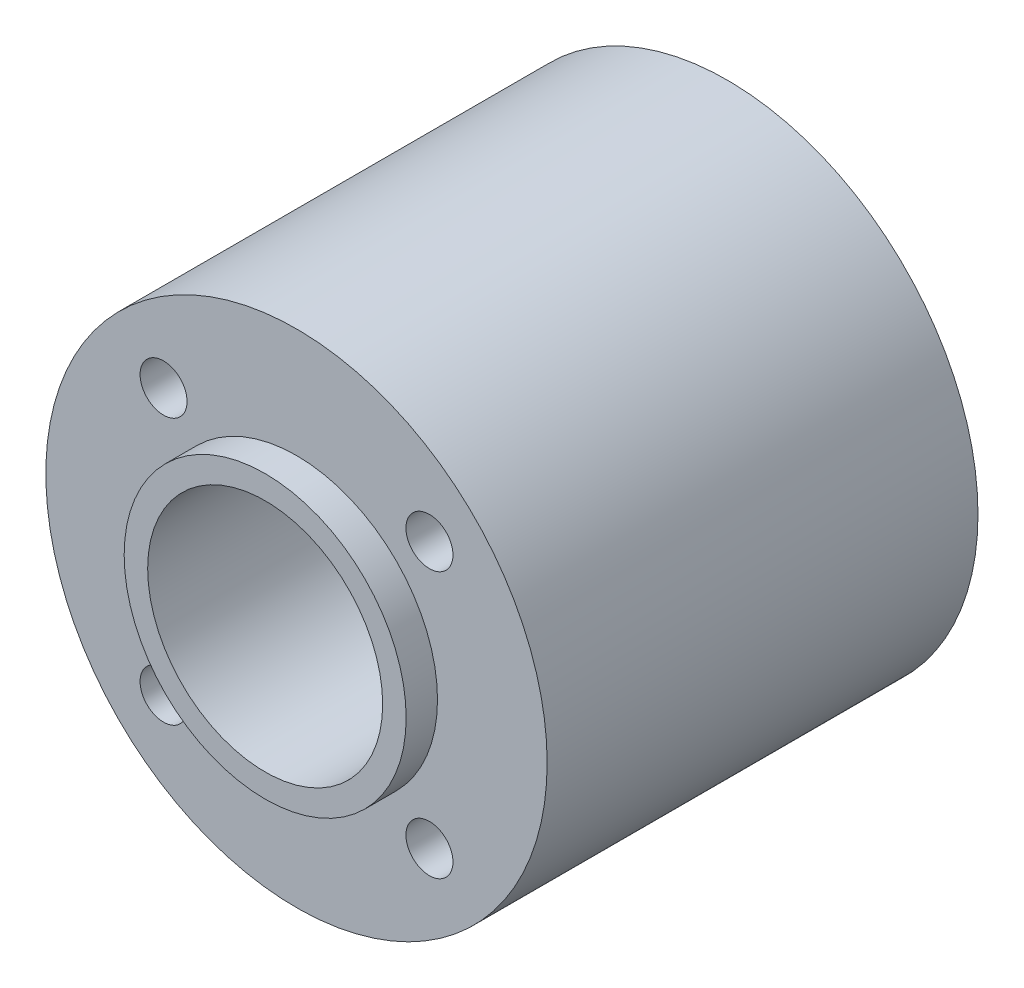
SolidWorks part; units mm, degrees
ref_plane "Ön Düzlem" through (0, 0, 0) normal (0, 0, 1) x (1, 0, 0)
ref_plane "Üst Düzlem" through (0, 0, 0) normal (0, 1, 0) x (1, 0, 0)
ref_plane "Sağ Düzlem" through (0, 0, 0) normal (1, 0, 0) x (0, 0, -1)
sketch "Çizim1" plane through (0, 0, 0) normal (0, 0, 1) x (1, 0, 0)
  line L0 (0, 0) -> (-8.4853, 8.4853) construction
  circle A0 centre (0, 0) radius 7.5
  circle A1 centre (0, 0) radius 16
  circle A2 centre (0, 0) radius 12 construction
  circle A3 centre (-8.4853, 8.4853) radius 1.5
  circle A4 centre (8.4853, 8.4853) radius 1.5
  circle A5 centre (8.4853, -8.4853) radius 1.5
  circle A6 centre (-8.4853, -8.4853) radius 1.5
  circle A7 centre (0, 0) radius 9
  point P16 (0, 0)
  dimension "D1" = 32
  dimension "D2" = 15
  dimension "D3" = 4
  dimension "D4" = 1.5
  dimension "D5" = 3
extrude "Yükseklik-Ekstrüzyon1" add sketch "Çizim1" along normal blind 27.5 contours A1 A7 A6 A5 A4 A3 | A7 A0
sketch "Çizim2" plane through (0, 0, 27.5) normal (0, 0, 1) x (1, 0, 0)
  circle A0 centre (0, 0) radius 9
  circle A1 centre (0, 0) radius 7.5
extrude "Yükseklik-Ekstrüzyon2" add sketch "Çizim2" along normal blind 2 and the other way blind 29.5
